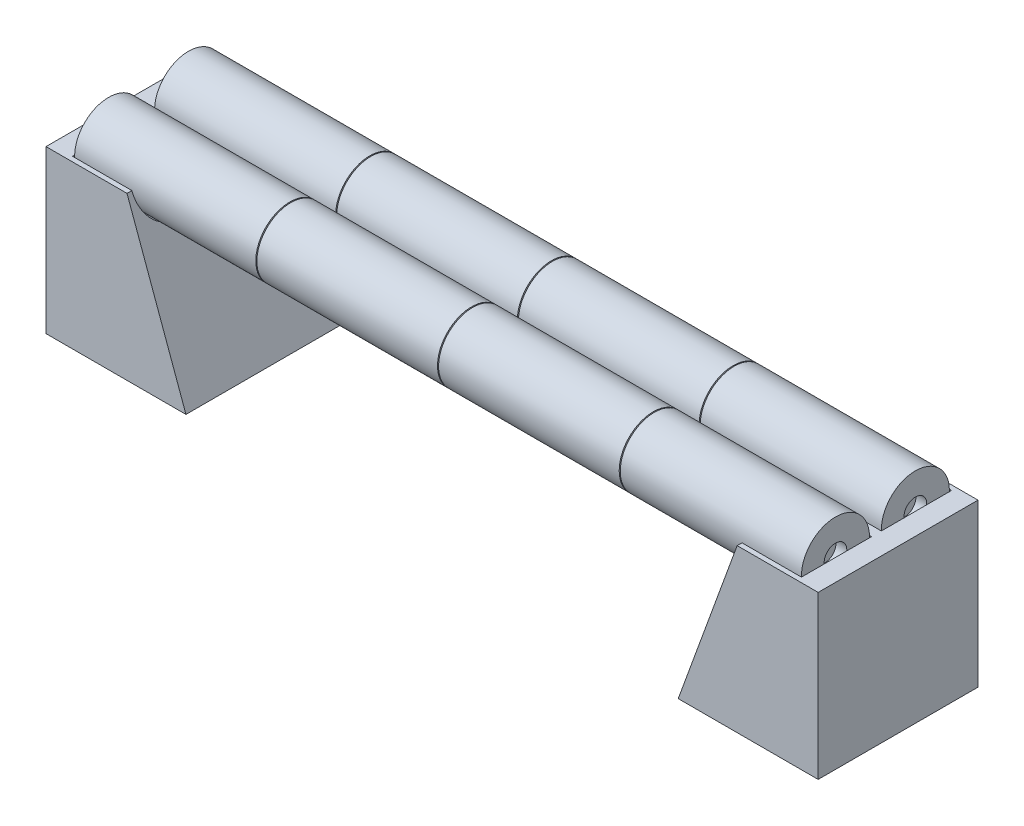
SolidWorks part; units mm, degrees
ref_plane "Front Plane" through (0, 0, 0) normal (0, 0, 1) x (1, 0, 0)
ref_plane "Top Plane" through (0, 0, 0) normal (0, 1, 0) x (1, 0, 0)
ref_plane "Right Plane" through (0, 0, 0) normal (1, 0, 0) x (0, 0, -1)
sketch "Sketch1" plane through (0, 0, 0) normal (0, 0, 1) x (1, 0, 0)
  line L0 (71.5, 0) -> (-71.5, 0) construction
  line L5 (-71.5, 0) -> (-71.5, 30)
  line L6 (-71.5, 30) -> (-56.5, 30)
  line L7 (-56.5, 30) -> (-45.5809, 0)
  line L8 (-45.5809, 0) -> (-71.5, 0)
  dimension "D1" = 143
  dimension "D2" = 30
  dimension "D3" = 20
  dimension "D4" = 15
extrude "Boss-Extrude1" add sketch "Sketch1" along normal mid plane 29.6
sketch "Sketch2" plane through (-71.5, 0, 0) normal (-1, 0, 0) x (0, 0, 1)
  line L1 (-14.8, 30) -> (0, 30) construction
  line L2 (14.8, 30) -> (-14.8, 30) construction
  line L3 (0, 30) -> (14.8, 30) construction
  circle A3 centre (-7.4, 30) radius 6.5
  circle A4 centre (7.4, 30) radius 6.5
  dimension "D1" = 13
extrude "Cut-Extrude1" cut sketch "Sketch2" against normal blind 29.6 from offset 4 offset against normal yes
mirror "Mirror3" about plane through (0, 0, 0) normal (1, 0, 0) of bodies 102
sketch "Sketch3" plane through (-67.5, 0, 0) normal (1, 0, 0) x (0, 0, -1)
  line L0 (-13.9, 30) -> (-0.9, 30) construction
  line L1 (0.9, 30) -> (13.9, 30) construction
  circle A0 centre (-7.4, 30) radius 6.3
  arc A1 (-13.9, 30) -> (-0.9, 30) centre (-7.4, 30) ccw construction
  circle A2 centre (7.4, 30) radius 6.3
  dimension "D1" = 0.2
extrude "Boss-Extrude2" add sketch "Sketch3" along normal offset from surface (134.6 mm away) 0.2 from offset 0.2 separate body up to face at (67.5, 26.75, -7.4)
sketch "Sketch4" plane through (0, 0, 0) normal (0, 0, 1) x (1, 0, 0)
  line L0 (-33.65, 44.9434) -> (-33.65, 10.215)
  line L1 (-33.65, 10.215) -> (33.65, 10.215)
  line L2 (33.65, 10.215) -> (33.65, 44.9434)
  line L3 (33.65, 44.9434) -> (0, 44.9434)
  line L4 (0, 44.9434) -> (0, 14.4401)
  line L5 (-67.3, 30) -> (-33.65, 30) construction
  line L6 (-67.3, 36.3) -> (-67.3, 23.7) construction
  line L7 (-33.65, 30) -> (0, 30) construction
  point P2 (0, 10.215)
extrude "Cut-Extrude-Thin1" cut sketch "Sketch4" against normal through all and the other way through all thin thin type mid plane wall 0.2
sketch "Sketch5" plane through (67.3, 0, 0) normal (1, 0, 0) x (0, 0, -1)
  circle A0 centre (-7.4, 30) radius 2.1
  circle A1 centre (7.4, 30) radius 2.1
  dimension "D1" = 4.2
extrude "Cut-Extrude2" cut sketch "Sketch5" against normal mid plane 4
pattern_linear "LPattern1" count 5 spacing 33.75 along (-1, 0, 0) of "Cut-Extrude2"
